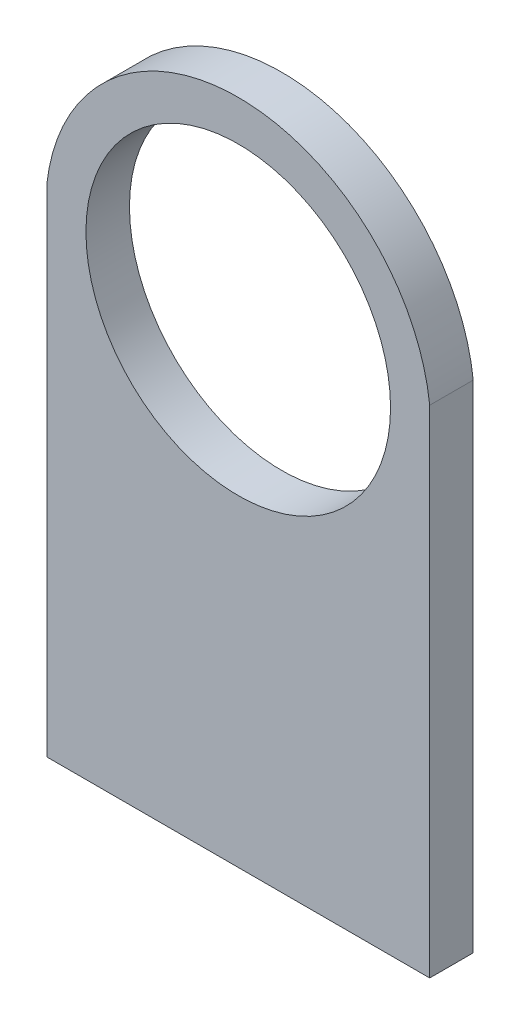
SolidWorks part; units mm, degrees
material "ABS"
ref_plane "Plan de face" through (0, 0, 0) normal (0, 0, 1) x (1, 0, 0)
ref_plane "Plan de dessus" through (0, 0, 0) normal (0, 1, 0) x (1, 0, 0)
ref_plane "Plan de droite" through (0, 0, 0) normal (1, 0, 0) x (0, 0, -1)
sketch "Esquisse1" plane through (0, 0, 0) normal (0, 0, 1) x (1, 0, 0)
  line L0 (0, 0) -> (0, -57)
  line L1 (0, -57) -> (44, -57)
  line L2 (44, -57) -> (44, 0)
  arc A0 (0, 0) -> (44, 0) centre (22, -2.5) cw
  circle A1 centre (22, -2.5) radius 17.5
extrude "Boss.-Extru.1" add sketch "Esquisse1" along normal blind 5
